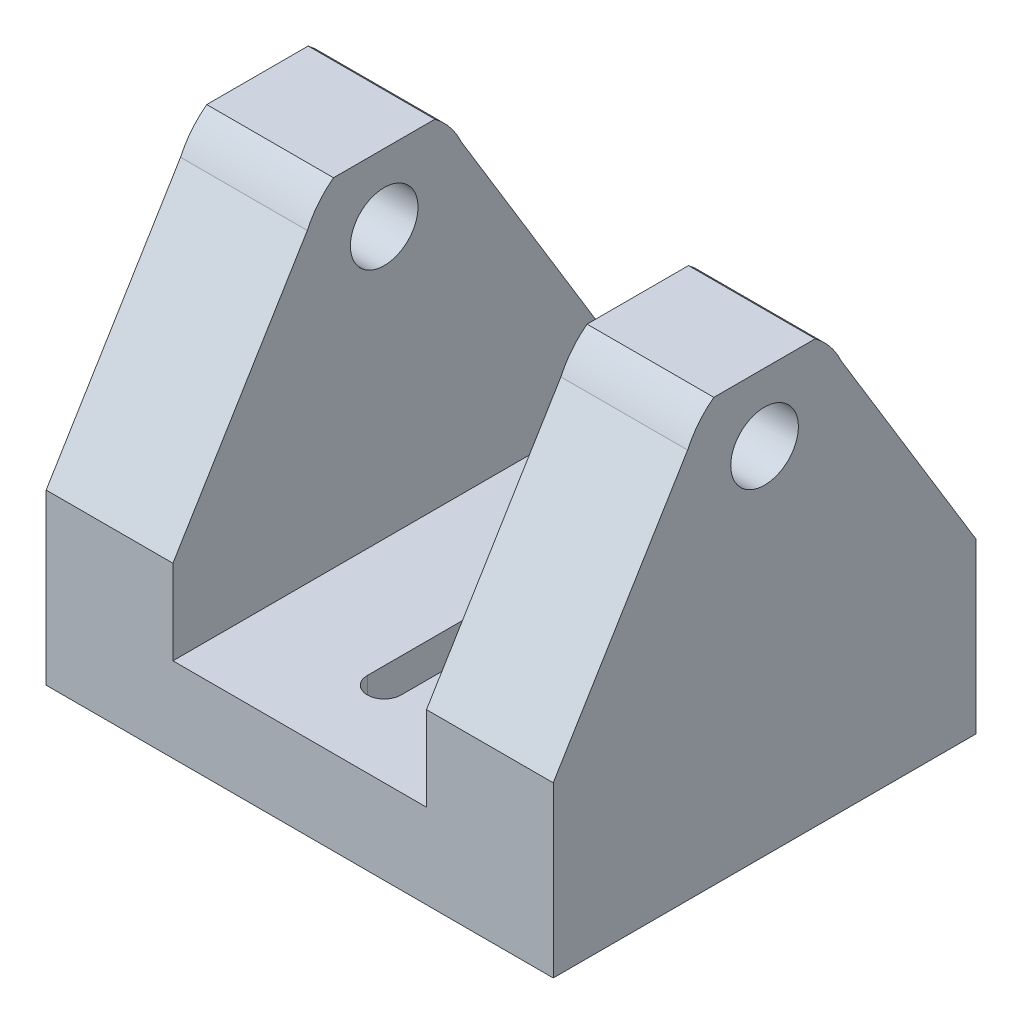
SolidWorks part; units mm, degrees
ref_plane "Front Plane" through (0, 0, 0) normal (0, 0, 1) x (1, 0, 0)
ref_plane "Top Plane" through (0, 0, 0) normal (0, 1, 0) x (1, 0, 0)
ref_plane "Right Plane" through (0, 0, 0) normal (1, 0, 0) x (0, 0, -1)
sketch "Sketch1" plane through (0, 0, 0) normal (0, 1, 0) x (1, 0, 0)
  line L1 (0, 0) -> (76.2, 0)
  line L2 (0, 0) -> (0, 63.5)
  line L3 (0, 63.5) -> (76.2, 63.5)
  line L4 (76.2, 0) -> (76.2, 63.5)
  dimension "D1" = 76.2
  dimension "D2" = 63.5
extrude "Boss-Extrude2" add sketch "Sketch1" along normal blind 63.5
sketch "Sketch6" plane through (0, 0, 0) normal (0, 0, 1) x (1, 0, 0)
  line L0 (0, 63.5) -> (76.2, 63.5) construction
  line L1 (19.05, 63.5) -> (57.15, 63.5)
  line L2 (19.05, 63.5) -> (19.05, 12.7)
  line L3 (19.05, 12.7) -> (57.15, 12.7)
  line L4 (57.15, 63.5) -> (57.15, 12.7)
  line L5 (0, 63.5) -> (0, 0) construction
  line L6 (76.2, 63.5) -> (76.2, 0) construction
  line L7 (0, 0) -> (76.2, 0) construction
  dimension "D1" = 19.05
  dimension "D2" = 19.05
  dimension "D3" = 12.7
extrude "Cut-Extrude4" cut sketch "Sketch6" against normal blind 63.5 contours L2 L1 L4 L3
sketch "Sketch7" plane through (0, 0, 0) normal (0, 1, 0) x (1, 0, 0)
  line L0 (38.1, 0) -> (38.1, 63.5)
  line L1 (0, 0) -> (76.2, 0) construction
  line L2 (76.2, 63.5) -> (0, 63.5) construction
extrude "Cut-Extrude6" cut sketch "Sketch7" against normal through all and the other way through all flip side to cut
mirror "Mirror3" about plane through (38.1, 226.5937, 0) normal (-1, 0, 0) of "Boss-Extrude2", "Cut-Extrude4"
sketch "Sketch9" plane through (0, 0, 0) normal (-1, 0, 0) x (0, 0, 1)
  line L1 (-63.5, 53.34) -> (0, 53.34) construction
  line L2 (-63.5, 63.5) -> (-63.5, 0) construction
  line L3 (0, 63.5) -> (0, 0) construction
  line L4 (-63.5, 63.5) -> (0, 63.5) construction
  circle A1 centre (-31.75, 53.34) radius 5.08
  dimension "D1" = 10.16
  dimension "D2" = 10.16
extrude "Cut-Extrude7" cut sketch "Sketch9" against normal through all contours A1
sketch "Sketch10" plane through (0, 0, 0) normal (-1, 0, 0) x (0, 0, 1)
  line L0 (-31.75, 53.34) -> (-44.45, 53.34) construction
  line L1 (-31.75, 53.34) -> (-19.05, 53.34) construction
  line L2 (-31.75, 53.34) -> (-31.75, 66.04) construction
  line L3 (-43.307, 58.6055) -> (-20.193, 58.6055) construction
  line L4 (-63.5, 25.4) -> (0, 25.4) construction
  line L5 (-63.5, 63.5) -> (-63.5, 0) construction
  line L6 (0, 63.5) -> (0, 0) construction
  line L7 (-63.5, 0) -> (0, 0) construction
  line L8 (-20.193, 58.6055) -> (0, 25.4)
  line L9 (-43.307, 58.6055) -> (-63.5, 25.4)
  line L10 (-63.5, 25.4) -> (0, 25.4)
  line L11 (-24.13, 63.5) -> (0, 63.5)
  line L12 (-63.5, 63.5) -> (0, 63.5) construction
  line L13 (0, 63.5) -> (0, 25.4)
  line L14 (-39.37, 63.5) -> (-63.5, 63.5)
  line L15 (-63.5, 63.5) -> (-63.5, 25.4)
  arc A0 (-43.307, 58.6055) -> (-20.193, 58.6055) centre (-31.75, 53.34) cw
  line M8 (0, 0) -> (0, 63.5)
  line M9 (0, 63.5) -> (-63.5, 63.5)
  line M10 (-63.5, 63.5) -> (-63.5, 0)
  dimension "D4" = 12.7
  dimension "D6" = 25.4
  dimension "D1" = 12.7
  dimension "D2" = 12.7
  dimension "D3" = 12.7
  dimension "D5" = 23.114
extrude "Cut-Extrude10" cut sketch "Sketch10" against normal through all contours L9 A0 M9 M10 | A0 L8 M9 M8
sketch "Sketch11" plane through (0, 0, 0) normal (0, 1, 0) x (1, 0, 0)
  line L0 (76.2, 31.75) -> (0, 31.75) construction
  line L1 (76.2, 63.5) -> (76.2, 0) construction
  line L2 (0, 63.5) -> (0, 0) construction
  line L3 (38.1, 63.5) -> (38.1, 0) construction
  line L4 (76.2, 63.5) -> (0, 63.5) construction
  line L5 (0, 0) -> (76.2, 0) construction
  line L6 (76.2, 50.8) -> (0, 50.8) construction
  line L7 (76.2, 12.7) -> (0, 12.7) construction
  line L8 (40.64, 50.8) -> (40.64, 12.7)
  line L9 (35.56, 50.8) -> (35.56, 12.7)
  arc A0 (40.64, 50.8) -> (35.56, 50.8) centre (38.1, 50.8) ccw
  arc A1 (40.64, 12.7) -> (35.56, 12.7) centre (38.1, 12.7) cw
  dimension "D1" = 12.7
  dimension "D2" = 12.7
  dimension "D3" = 2.54
  dimension "D4" = 2.54
extrude "Cut-Extrude15" cut sketch "Sketch11" against normal through all and the other way through all contours A1 L9 A0 L8
